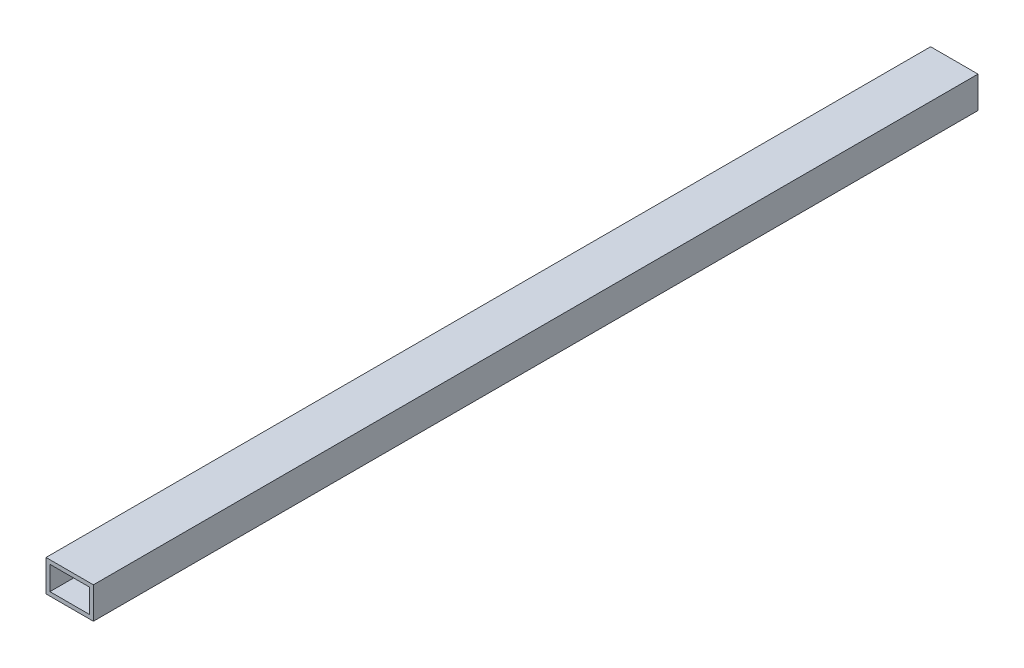
SolidWorks part; units mm, degrees
ref_plane "Front Plane" through (0, 0, 0) normal (0, 0, 1) x (1, 0, 0)
ref_plane "Top Plane" through (0, 0, 0) normal (0, 1, 0) x (1, 0, 0)
ref_plane "Right Plane" through (0, 0, 0) normal (1, 0, 0) x (0, 0, -1)
sketch "Sketch1" plane through (0, 0, 0) normal (0, 0, 1) x (1, 0, 0)
  line L1 (-19.05, 12.7) -> (19.05, 12.7)
  line L2 (-19.05, 12.7) -> (-19.05, -12.7)
  line L3 (-19.05, -12.7) -> (19.05, -12.7)
  line L4 (19.05, 12.7) -> (19.05, -12.7)
  line L5 (-19.05, 12.7) -> (19.05, -12.7) construction
  line L6 (-19.05, -12.7) -> (19.05, 12.7) construction
  point P0 (0, 0)
  dimension "D1" = 38.1
  dimension "D2" = 25.4
extrude "Boss-Extrude1" add sketch "Sketch1" along normal blind 711.2
shell "Shell1" thickness 3.175
